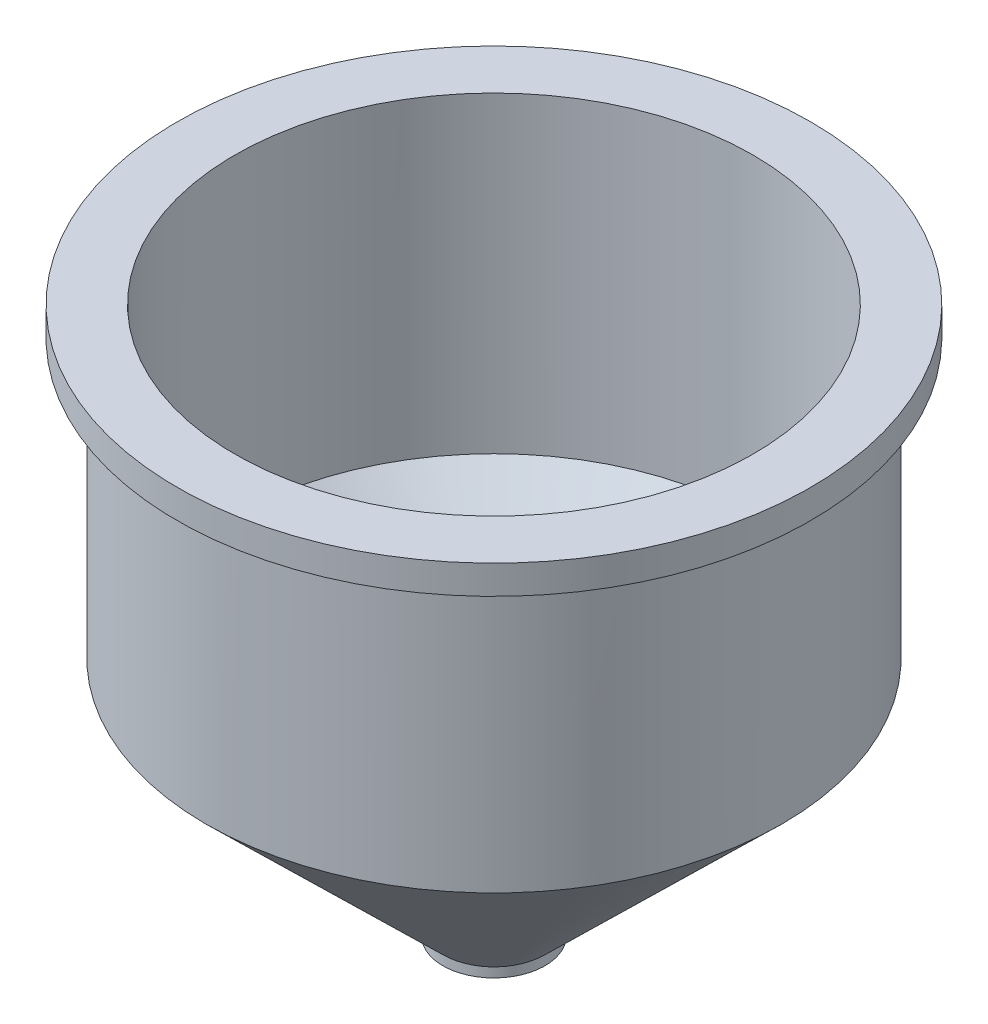
SolidWorks part; units mm, degrees
ref_plane "前视基准面" through (0, 0, 0) normal (0, 0, 1) x (1, 0, 0)
ref_plane "上视基准面" through (0, 0, 0) normal (0, 1, 0) x (1, 0, 0)
ref_plane "右视基准面" through (0, 0, 0) normal (1, 0, 0) x (0, 0, -1)
other "Configuration Table"
sketch "草图1" plane through (0, 0, 0) normal (0, 0, 1) x (1, 0, 0)
  line L0 (0, -69.9734) -> (0, 52.3018) construction
  line L1 (0, -57) -> (5.3291, -57)
  line L2 (5.3291, -57) -> (5.3291, -56)
  line L3 (5.3291, -56) -> (30, -31.8855)
  line L4 (30, -31.8855) -> (30, -3)
  line L5 (30, -3) -> (33, -3)
  line L6 (33, -3) -> (33, 0)
  line L7 (33, 0) -> (27, 0)
  line L8 (27, 0) -> (27, -32.5478)
  line L11 (0, -56) -> (0, -57)
  line L12 (0, -56) -> (3.8, -56)
  line L13 (3.8, -56) -> (3.8, -51)
  line L14 (3.8, -51) -> (7.8, -51)
  line L15 (7.8, -51) -> (27, -32.5478)
  dimension "D1" = 3
  dimension "D2" = 3
  dimension "D3" = 3.8
  dimension "D4" = 57
  dimension "D5" = 1
  dimension "D6" = 6
  dimension "D7" = 27
  dimension "D8" = 5
  dimension "D9" = 4
revolve "旋转2" add sketch "草图1" angle 360 about L0
